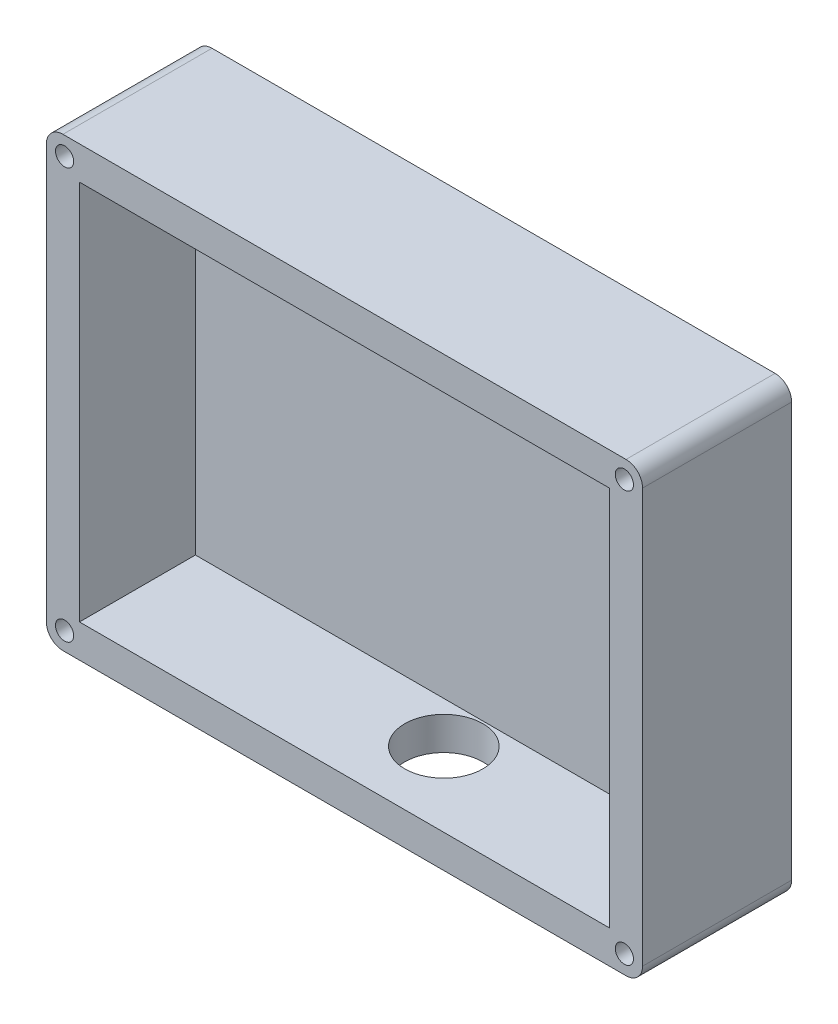
SolidWorks part; units mm, degrees
ref_plane "Front Plane" through (0, 0, 0) normal (0, 0, 1) x (1, 0, 0)
ref_plane "Top Plane" through (0, 0, 0) normal (0, 1, 0) x (1, 0, 0)
ref_plane "Right Plane" through (0, 0, 0) normal (1, 0, 0) x (0, 0, -1)
sketch "Sketch1" plane through (0, 0, 0) normal (0, 0, 1) x (1, 0, 0)
  line L1 (0, 0) -> (91.44, 0)
  line L2 (0, 0) -> (0, -68.58)
  line L3 (0, -68.58) -> (91.44, -68.58)
  line L4 (91.44, 0) -> (91.44, -68.58)
  dimension "D1" = 91.44
  dimension "D2" = 68.58
extrude "Boss-Extrude1" add sketch "Sketch1" along normal blind 22.86
shell "Shell1" thickness 5.08
sketch "Sketch2" plane through (0, 0, 22.86) normal (0, 0, 1) x (1, 0, 0)
  line L0 (0, 0) -> (0, -68.58) construction
  line L1 (91.44, 0) -> (0, 0) construction
  line L2 (91.44, -68.58) -> (91.44, 0) construction
  line L4 (0, -68.58) -> (91.44, -68.58) construction
  circle A0 centre (2.794, -2.794) radius 1.397
  circle A1 centre (88.646, -2.794) radius 1.397
  circle A2 centre (88.646, -65.786) radius 1.397
  circle A3 centre (2.794, -65.786) radius 1.397
  point P14 (0, 0)
  point P16 (88.9146, -68.58)
  dimension "D1" = 2.794
  dimension "D2" = 2.794
  dimension "D3" = 2.794
  dimension "D4" = 2.794
  dimension "D5" = 2.794
  dimension "D6" = 2.794
  dimension "D7" = 2.794
  dimension "D8" = 2.794
  dimension "D9" = 2.794
extrude "Cut-Extrude1" cut sketch "Sketch2" against normal blind 8.0645
fillet "Fillet1" radius 2.54 4 edges at (0, -68.58, 11.43) (0, 0, 11.43) (91.44, 0, 11.43) (91.44, -68.58, 11.43)
sketch "Sketch3" plane through (0, -68.58, 0) normal (0, -1, 0) x (-1, 0, 0)
  line L0 (-91.44, -22.86) -> (-91.44, 0) construction
  line L1 (-2.54, 0) -> (-88.9, 0) construction
  circle A0 centre (-49.53, -11.43) radius 6
  point P4 (0, 0)
  dimension "D3" = 12
  dimension "D1" = 41.91
  dimension "D2" = 11.43
extrude "Cut-Extrude2" cut sketch "Sketch3" against normal up to surface (5.08 mm away) up to face at (45.72, -63.5, 13.97)
sketch "Sketch4" plane through (0, 0, 0) normal (0, 0, -1) x (-1, 0, 0)
  line L1 (-20.32, -42.2275) -> (-71.12, -42.2275)
  line L2 (-20.32, -42.2275) -> (-20.32, -26.3525)
  line L3 (-20.32, -26.3525) -> (-71.12, -26.3525)
  line L4 (-71.12, -42.2275) -> (-71.12, -26.3525)
  line L5 (0, -2.54) -> (0, -66.04) construction
  line L6 (-88.9, 0) -> (-2.54, 0) construction
  dimension "D1" = 50.8
  dimension "D2" = 15.875
  dimension "D3" = 20.32
  dimension "D4" = 26.3525
extrude "Boss-Extrude2" add sketch "Sketch4" along normal blind 20.32
sketch "Sketch5" plane through (0, -42.2275, 0) normal (0, -1, 0) x (1, 0, 0)
  line L0 (71.12, -20.32) -> (20.32, -20.32) construction
  circle A0 centre (45.72, -20.32) radius 12.9921
  dimension "D1" = 25.9842
extrude "Cut-Extrude3" cut sketch "Sketch5" against normal through all
sketch "Sketch6" plane through (0, 0, -20.32) normal (0, 0, -1) x (-1, 0, 0)
  line L0 (-32.7279, -42.2275) -> (-32.7279, -26.3525) construction
  line L1 (-71.12, -26.3525) -> (-71.12, -42.2275) construction
  line L2 (-20.32, -26.3525) -> (-32.7279, -26.3525) construction
  line L3 (-58.7121, -26.3525) -> (-71.12, -26.3525) construction
  circle A0 centre (-26.5176, -34.29) radius 1.27
  circle A1 centre (-64.9097, -34.29) radius 1.27
  point P6 (0, 0)
  dimension "D5" = 2.54
  dimension "D1" = 6.2103
  dimension "D2" = 6.2103
  dimension "D3" = 7.9375
  dimension "D4" = 7.9375
extrude "Cut-Extrude4" cut sketch "Sketch6" against normal blind 12.6238
fillet "Fillet2" radius 2.54 4 edges at (20.32, -34.29, 0) (45.72, -42.2275, 0) (71.12, -34.29, 0) (45.72, -26.3525, 0)
